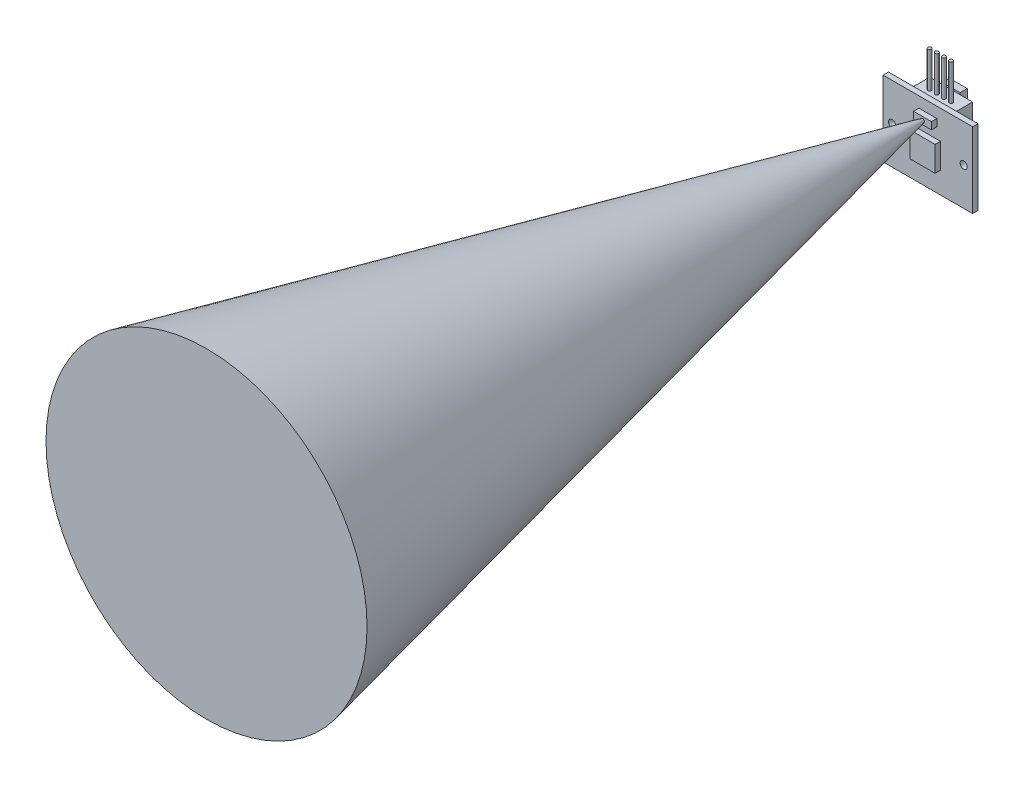
SolidWorks part; units mm, degrees
ref_plane "Plan de face" through (0, 0, 0) normal (0, 0, 1) x (1, 0, 0)
ref_plane "Plan de dessus" through (0, 0, 0) normal (0, 1, 0) x (1, 0, 0)
ref_plane "Plan de droite" through (0, 0, 0) normal (1, 0, 0) x (0, 0, -1)
sketch "Esquisse1" plane through (0, 0, 0) normal (0, 0, 1) x (1, 0, 0)
  line L0 (0, 10.5) -> (0, -10.5) construction
  line L1 (-12.5, -10.5) -> (12.5, -10.5)
  line L2 (-12.5, -10.5) -> (-12.5, 10.5)
  line L3 (-12.5, 10.5) -> (12.5, 10.5)
  line L4 (12.5, -10.5) -> (12.5, 10.5)
  circle A0 centre (-10, 0) radius 1
  circle A1 centre (10, 0) radius 1
  dimension "D3" = 20
  dimension "D4" = 2
  dimension "D1" = 25
  dimension "D2" = 21
extrude "Boss.-Extru.1" add sketch "Esquisse1" along normal blind 1.5
sketch "Esquisse2" plane through (0, 0, 0) normal (0, 0, -1) x (-1, 0, 0)
  line L1 (-6, 10) -> (6, 10)
  line L2 (-6, 10) -> (-6, 0)
  line L3 (-6, 0) -> (6, 0)
  line L4 (6, 10) -> (6, 0)
  dimension "D1" = 12
  dimension "D2" = 10
extrude "Boss.-Extru.2" add sketch "Esquisse2" along normal blind 5 separate body
sketch "Esquisse3" plane through (0, 0, 1.5) normal (0, 0, 1) x (1, 0, 0)
  line L0 (-12.5, 10.5) -> (-12.5, -10.5) construction
  line L1 (-2.5, 7.5) -> (2.5, 7.5)
  line L2 (-2.5, 7.5) -> (-2.5, 5.5)
  line L3 (-2.5, 5.5) -> (2.5, 5.5)
  line L4 (2.5, 7.5) -> (2.5, 5.5)
  line L5 (-3.5, 2.5) -> (3.5, 2.5)
  line L6 (-3.5, 2.5) -> (-3.5, -4.5)
  line L7 (-3.5, -4.5) -> (3.5, -4.5)
  line L8 (3.5, 2.5) -> (3.5, -4.5)
  line L9 (12.5, -10.5) -> (12.5, 10.5) construction
  line L10 (12.5, 10.5) -> (-12.5, 10.5) construction
  line L11 (-12.5, -10.5) -> (12.5, -10.5) construction
  dimension "D1" = 10
  dimension "D2" = 10
  dimension "D3" = 5
  dimension "D4" = 3
  dimension "D5" = 16
  dimension "D6" = 2
  dimension "D7" = 9
  dimension "D8" = 9
  dimension "D9" = 7
  dimension "D10" = 7
  dimension "D11" = 6
  dimension "D12" = 3
extrude "Boss.-Extru.3" add sketch "Esquisse3" along normal blind 1.5 separate body
sketch "Esquisse4" plane through (0, 0, -5) normal (0, 0, -1) x (-1, 0, 0)
  line L0 (-12.5, 10.5) -> (12.5, 10.5) construction
  line L1 (-2.5, 10.5) -> (2.5, 10.5)
  line L2 (-2.5, 10.5) -> (-2.5, 2.5)
  line L3 (-2.5, 2.5) -> (2.5, 2.5)
  line L4 (2.5, 10.5) -> (2.5, 2.5)
  point P6 (0, 2.5)
  dimension "D1" = 5
  dimension "D2" = 8
extrude "Boss.-Extru.4" add sketch "Esquisse4" along normal blind 2
sketch "Esquisse5" plane through (0, 10, 0) normal (0, 1, 0) x (1, 0, 0)
  line L0 (-6, 0) -> (6, 0) construction
  circle A0 centre (-3, 2) radius 0.5
  circle A1 centre (-1, 2) radius 0.5
  circle A2 centre (1, 2) radius 0.5
  circle A3 centre (3, 2) radius 0.5
  dimension "D1" = 4
  dimension "D2" = 6
  dimension "D3" = 3
  dimension "D4" = 1
  dimension "D5" = 2
extrude "Boss.-Extru.5" add sketch "Esquisse5" along normal blind 10 separate body
sketch "Esquisse6" plane through (0, 0, 3) normal (0, 0, 1) x (1, 0, 0)
  line L0 (2.5, 7.5) -> (-2.5, 5.5) construction
  circle A0 centre (0, 6.5) radius 0.5
  dimension "D1" = 1
extrude "Boss.-Extru.6" add sketch "Esquisse6" along normal blind 200 draft 12.5 separate body draft outward yes
